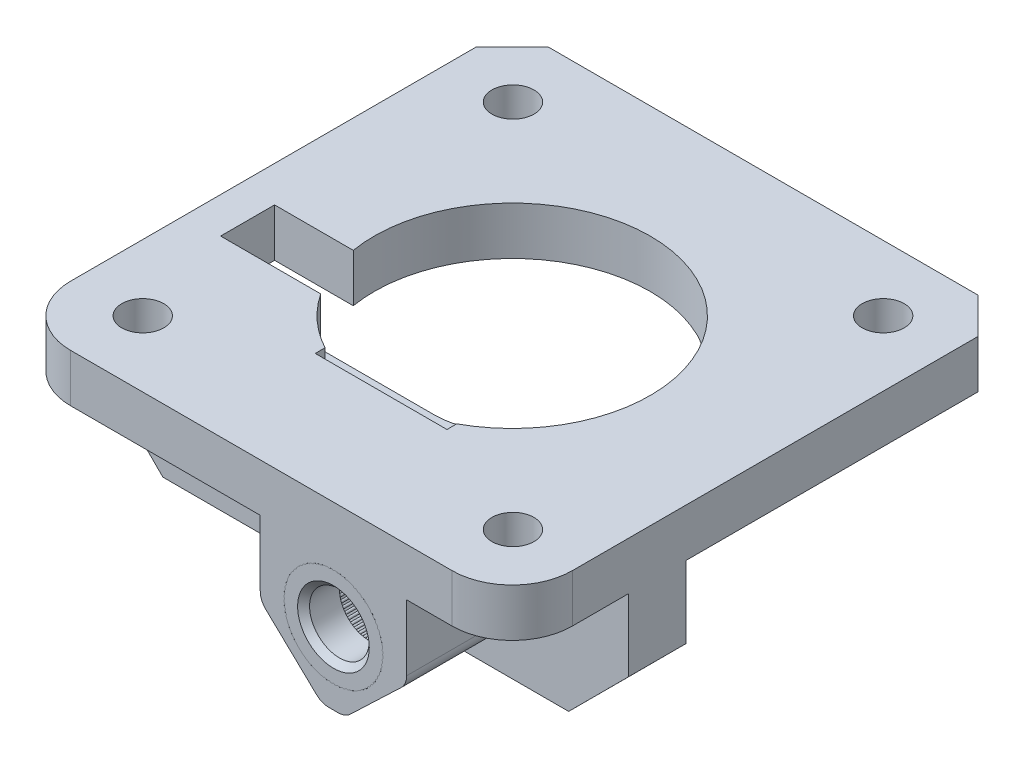
SolidWorks part; units mm, degrees
material "1060 Alloy"
ref_plane "Front Plane" through (0, 0, 0) normal (0, 0, 1) x (1, 0, 0)
ref_plane "Top Plane" through (0, 0, 0) normal (0, 1, 0) x (1, 0, 0)
ref_plane "Right Plane" through (0, 0, 0) normal (1, 0, 0) x (0, 0, -1)
sketch "Sketch2" plane through (0, 0, 0) normal (0, 1, 0) x (1, 0, 0)
  line L0 (-21, 18.0019) -> (-18.0019, 21)
  line L1 (18.0019, 21) -> (-18.0019, 21)
  line L2 (21, 18.0019) -> (21, -15.97)
  line L3 (15.97, -21) -> (-15.97, -21)
  line L4 (-21, 18.0019) -> (-21, -15.97)
  line L5 (19.5009, 19.5009) -> (-21, -21) construction
  line L6 (21, -21) -> (-19.5009, 19.5009) construction
  line L7 (18.0019, 21) -> (21, 18.0019)
  line L8 (-5.5162, -10.979) -> (5.5162, -10.979)
  line L9 (-5.5162, -10.979) -> (-5.5162, -10.159)
  line L10 (5.5162, -10.979) -> (5.5162, -10.159)
  line L11 (-17.99, -1.91) -> (-17.99, -6.43)
  line L12 (-17.99, -1.91) -> (-11.4011, -1.91)
  line L13 (-17.99, -6.43) -> (-9.6067, -6.43)
  arc A1 (21, -15.97) -> (15.97, -21) centre (15.97, -15.97) cw
  arc A2 (-15.97, -21) -> (-21, -15.97) centre (-15.97, -15.97) cw
  circle A4 centre (-15.47, 15.53) radius 1.76
  circle A5 centre (15.53, 15.53) radius 1.76
  circle A6 centre (-15.47, -15.47) radius 1.76
  circle A7 centre (15.53, -15.47) radius 1.76
  arc A8 (5.5162, -10.159) -> (-11.4011, -1.91) centre (0, 0) ccw
  arc A9 (-9.6067, -6.43) -> (-5.5162, -10.159) centre (0, 0) ccw
  point P0 (0, 0)
  point P10 (-19.5009, 19.5009)
  point P11 (19.5009, 19.5009)
  point P30 (0, -10.979)
  dimension "D7" = 5.03
  dimension "D8" = 3.52
  dimension "D11" = 3.52
  dimension "D12" = 5.47
  dimension "D13" = 5.47
  dimension "D14" = 3.52
  dimension "D15" = 3.52
  dimension "D16" = 5.53
  dimension "D17" = 5.53
  dimension "D20" = 23.12
  dimension "D1" = 42
  dimension "D2" = 4.24
  dimension "D3" = 4.24
  dimension "D4" = 45
  dimension "D5" = 36.0037
  dimension "D6" = 39.0019
  dimension "D9" = 5.53
  dimension "D10" = 5.47
  dimension "D18" = 5.47
  dimension "D19" = 5.53
  dimension "D21" = 11.0324
  dimension "D22" = 0.82
  dimension "D23" = 4.52
  dimension "D24" = 14.57
  dimension "D25" = 3.01
extrude "Boss-Extrude1" add sketch "Sketch2" along normal blind 4.02
ref_plane "Plane1" through (0, 0, 21) normal (0, 0, 1) x (1, 0, 0)
sketch "Sketch4" plane through (0, 0, 21) normal (0, 0, 1) x (1, 0, 0)
  line L0 (-21, 4.02) -> (-21, 0) construction
  line L1 (-15.97, 4.02) -> (15.97, 4.02) construction
  line L2 (12.16, 0) -> (12.16, -5.505)
  line L3 (7.4523, -10.6426) -> (11.6923, -6.5976)
  line L4 (6.41, -11.06) -> (5.65, -11.06)
  line L5 (4.6077, -10.6426) -> (0.3677, -6.5976)
  line L6 (-0.1, -5.505) -> (-0.1, 0)
  line L7 (-15.97, 0) -> (15.97, 0) construction
  line L8 (-0.1, 0) -> (12.16, 0)
  arc A0 (6.4951, -9.1539) -> (6.6481, -9.1337) centre (6.03, -5.03) ccw
  arc A1 (12.16, -5.505) -> (11.6923, -6.5976) centre (10.65, -5.505) cw
  arc A2 (7.4523, -10.6426) -> (6.41, -11.06) centre (6.41, -9.55) cw
  arc A3 (5.65, -11.06) -> (4.6077, -10.6426) centre (5.65, -9.55) cw
  arc A4 (0.3677, -6.5976) -> (-0.1, -5.505) centre (1.41, -5.505) cw
  arc A5 (6.1339, -9.1787) -> (5.9261, -9.1787) centre (6.03, -9.2387) ccw
  arc A6 (5.7719, -9.172) -> (5.5649, -9.1539) centre (5.6632, -9.2227) ccw
  arc A7 (5.4119, -9.1337) -> (5.2073, -9.0976) centre (5.2992, -9.1748) ccw
  arc A8 (5.0566, -9.0642) -> (4.8559, -9.0104) centre (4.9407, -9.0953) ccw
  arc A9 (4.7087, -8.964) -> (4.5134, -8.893) centre (4.5905, -8.9849) ccw
  arc A10 (4.3709, -8.8339) -> (4.1825, -8.7461) centre (4.2513, -8.8444) ccw
  arc A11 (4.0456, -8.6748) -> (3.8657, -8.5709) centre (3.9256, -8.6749) ccw
  arc A12 (3.7355, -8.488) -> (3.5653, -8.3688) centre (3.616, -8.4776) ccw
  arc A13 (3.4429, -8.2749) -> (3.2837, -8.1413) centre (3.3247, -8.2541) ccw
  arc A14 (3.1699, -8.0371) -> (3.0229, -7.8901) centre (3.054, -8.006) ccw
  arc A15 (2.9187, -7.7763) -> (2.7851, -7.6171) centre (2.8059, -7.7353) ccw
  arc A16 (2.6912, -7.4947) -> (2.572, -7.3245) centre (2.5824, -7.444) ccw
  arc A17 (2.4891, -7.1943) -> (2.3852, -7.0144) centre (2.3851, -7.1344) ccw
  arc A18 (2.3139, -6.8775) -> (2.2261, -6.6891) centre (2.2156, -6.8087) ccw
  arc A19 (2.167, -6.5466) -> (2.096, -6.3513) centre (2.0751, -6.4695) ccw
  arc A20 (2.0496, -6.2041) -> (1.9958, -6.0034) centre (1.9647, -6.1193) ccw
  arc A21 (1.9624, -5.8527) -> (1.9263, -5.6481) centre (1.8852, -5.7608) ccw
  arc A22 (1.9061, -5.4951) -> (1.888, -5.2881) centre (1.8373, -5.3968) ccw
  arc A23 (1.8813, -5.1339) -> (1.8813, -4.9261) centre (1.8213, -5.03) ccw
  arc A24 (1.888, -4.7719) -> (1.9061, -4.5649) centre (1.8373, -4.6632) ccw
  arc A25 (1.9263, -4.4119) -> (1.9624, -4.2073) centre (1.8852, -4.2992) ccw
  arc A26 (1.9958, -4.0566) -> (2.0496, -3.8559) centre (1.9647, -3.9407) ccw
  arc A27 (2.096, -3.7087) -> (2.167, -3.5134) centre (2.0751, -3.5905) ccw
  arc A28 (2.2261, -3.3709) -> (2.3139, -3.1825) centre (2.2156, -3.2513) ccw
  arc A29 (2.3852, -3.0456) -> (2.4891, -2.8657) centre (2.3851, -2.9256) ccw
  arc A30 (2.572, -2.7355) -> (2.6912, -2.5653) centre (2.5824, -2.616) ccw
  arc A31 (2.7851, -2.4429) -> (2.9187, -2.2837) centre (2.8059, -2.3247) ccw
  arc A32 (3.0229, -2.1699) -> (3.1699, -2.0229) centre (3.054, -2.054) ccw
  arc A33 (3.2837, -1.9187) -> (3.4429, -1.7851) centre (3.3247, -1.8059) ccw
  arc A34 (3.5653, -1.6912) -> (3.7355, -1.572) centre (3.616, -1.5824) ccw
  arc A35 (3.8657, -1.4891) -> (4.0456, -1.3852) centre (3.9256, -1.3851) ccw
  arc A36 (4.1825, -1.3139) -> (4.3709, -1.2261) centre (4.2513, -1.2156) ccw
  arc A37 (4.5134, -1.167) -> (4.7087, -1.096) centre (4.5905, -1.0751) ccw
  arc A38 (4.8559, -1.0496) -> (5.0566, -0.9958) centre (4.9407, -0.9647) ccw
  arc A39 (5.2073, -0.9624) -> (5.4119, -0.9263) centre (5.2992, -0.8852) ccw
  arc A40 (5.5649, -0.9061) -> (5.7719, -0.888) centre (5.6632, -0.8373) ccw
  arc A41 (5.9261, -0.8813) -> (6.1339, -0.8813) centre (6.03, -0.8213) ccw
  arc A42 (6.2881, -0.888) -> (6.4951, -0.9061) centre (6.3968, -0.8373) ccw
  arc A43 (6.6481, -0.9263) -> (6.8527, -0.9624) centre (6.7608, -0.8852) ccw
  arc A44 (7.0034, -0.9958) -> (7.2041, -1.0496) centre (7.1193, -0.9647) ccw
  arc A45 (7.3513, -1.096) -> (7.5466, -1.167) centre (7.4695, -1.0751) ccw
  arc A46 (7.6891, -1.2261) -> (7.8775, -1.3139) centre (7.8087, -1.2156) ccw
  arc A47 (8.0144, -1.3852) -> (8.1943, -1.4891) centre (8.1344, -1.3851) ccw
  arc A48 (8.3245, -1.572) -> (8.4947, -1.6912) centre (8.444, -1.5824) ccw
  arc A49 (8.6171, -1.7851) -> (8.7763, -1.9187) centre (8.7353, -1.8059) ccw
  arc A50 (8.8901, -2.0229) -> (9.0371, -2.1699) centre (9.006, -2.054) ccw
  arc A51 (9.1413, -2.2837) -> (9.2749, -2.4429) centre (9.2541, -2.3247) ccw
  arc A52 (9.3688, -2.5653) -> (9.488, -2.7355) centre (9.4776, -2.616) ccw
  arc A53 (9.5709, -2.8657) -> (9.6748, -3.0456) centre (9.6749, -2.9256) ccw
  arc A54 (9.7461, -3.1825) -> (9.8339, -3.3709) centre (9.8444, -3.2513) ccw
  arc A55 (9.893, -3.5134) -> (9.964, -3.7087) centre (9.9849, -3.5905) ccw
  arc A56 (10.0104, -3.8559) -> (10.0642, -4.0566) centre (10.0953, -3.9407) ccw
  arc A57 (10.0976, -4.2073) -> (10.1337, -4.4119) centre (10.1748, -4.2992) ccw
  arc A58 (10.1539, -4.5649) -> (10.172, -4.7719) centre (10.2227, -4.6632) ccw
  arc A59 (10.1787, -4.9261) -> (10.1787, -5.1339) centre (10.2387, -5.03) ccw
  arc A60 (10.172, -5.2881) -> (10.1539, -5.4951) centre (10.2227, -5.3968) ccw
  arc A61 (10.1337, -5.6481) -> (10.0976, -5.8527) centre (10.1748, -5.7608) ccw
  arc A62 (10.0642, -6.0034) -> (10.0104, -6.2041) centre (10.0953, -6.1193) ccw
  arc A63 (9.964, -6.3513) -> (9.893, -6.5466) centre (9.9849, -6.4695) ccw
  arc A64 (9.8339, -6.6891) -> (9.7461, -6.8775) centre (9.8444, -6.8087) ccw
  arc A65 (9.6748, -7.0144) -> (9.5709, -7.1943) centre (9.6749, -7.1344) ccw
  arc A66 (9.488, -7.3245) -> (9.3688, -7.4947) centre (9.4776, -7.444) ccw
  arc A67 (9.2749, -7.6171) -> (9.1413, -7.7763) centre (9.2541, -7.7353) ccw
  arc A68 (9.0371, -7.8901) -> (8.8901, -8.0371) centre (9.006, -8.006) ccw
  arc A69 (8.7763, -8.1413) -> (8.6171, -8.2749) centre (8.7353, -8.2541) ccw
  arc A70 (8.4947, -8.3688) -> (8.3245, -8.488) centre (8.444, -8.4776) ccw
  arc A71 (8.1943, -8.5709) -> (8.0144, -8.6748) centre (8.1344, -8.6749) ccw
  arc A72 (7.8775, -8.7461) -> (7.6891, -8.8339) centre (7.8087, -8.8444) ccw
  arc A73 (7.5466, -8.893) -> (7.3513, -8.964) centre (7.4695, -8.9849) ccw
  arc A74 (7.2041, -9.0104) -> (7.0034, -9.0642) centre (7.1193, -9.0953) ccw
  arc A75 (6.8527, -9.0976) -> (6.6481, -9.1337) centre (6.7608, -9.1748) ccw
  arc A76 (6.4951, -9.1539) -> (6.2881, -9.172) centre (6.3968, -9.2227) ccw
  arc A77 (6.8527, -9.0976) -> (7.0034, -9.0642) centre (6.03, -5.03) ccw
  arc A78 (6.1339, -9.1787) -> (6.2881, -9.172) centre (6.03, -5.03) ccw
  arc A79 (5.7719, -9.172) -> (5.9261, -9.1787) centre (6.03, -5.03) ccw
  arc A80 (5.4119, -9.1337) -> (5.5649, -9.1539) centre (6.03, -5.03) ccw
  arc A81 (5.0566, -9.0642) -> (5.2073, -9.0976) centre (6.03, -5.03) ccw
  arc A82 (4.7087, -8.964) -> (4.8559, -9.0104) centre (6.03, -5.03) ccw
  arc A83 (4.3709, -8.8339) -> (4.5134, -8.893) centre (6.03, -5.03) ccw
  arc A84 (4.0456, -8.6748) -> (4.1825, -8.7461) centre (6.03, -5.03) ccw
  arc A85 (3.7355, -8.488) -> (3.8657, -8.5709) centre (6.03, -5.03) ccw
  arc A86 (3.4429, -8.2749) -> (3.5653, -8.3688) centre (6.03, -5.03) ccw
  arc A87 (3.1699, -8.0371) -> (3.2837, -8.1413) centre (6.03, -5.03) ccw
  arc A88 (2.9187, -7.7763) -> (3.0229, -7.8901) centre (6.03, -5.03) ccw
  arc A89 (2.6912, -7.4947) -> (2.7851, -7.6171) centre (6.03, -5.03) ccw
  arc A90 (2.4891, -7.1943) -> (2.572, -7.3245) centre (6.03, -5.03) ccw
  arc A91 (2.3139, -6.8775) -> (2.3852, -7.0144) centre (6.03, -5.03) ccw
  arc A92 (2.167, -6.5466) -> (2.2261, -6.6891) centre (6.03, -5.03) ccw
  arc A93 (2.0496, -6.2041) -> (2.096, -6.3513) centre (6.03, -5.03) ccw
  arc A94 (1.9624, -5.8527) -> (1.9958, -6.0034) centre (6.03, -5.03) ccw
  arc A95 (1.9061, -5.4951) -> (1.9263, -5.6481) centre (6.03, -5.03) ccw
  arc A96 (1.8813, -5.1339) -> (1.888, -5.2881) centre (6.03, -5.03) ccw
  arc A97 (1.888, -4.7719) -> (1.8813, -4.9261) centre (6.03, -5.03) ccw
  arc A98 (1.9263, -4.4119) -> (1.9061, -4.5649) centre (6.03, -5.03) ccw
  arc A99 (1.9958, -4.0566) -> (1.9624, -4.2073) centre (6.03, -5.03) ccw
  arc A100 (2.096, -3.7087) -> (2.0496, -3.8559) centre (6.03, -5.03) ccw
  arc A101 (2.2261, -3.3709) -> (2.167, -3.5134) centre (6.03, -5.03) ccw
  arc A102 (2.3852, -3.0456) -> (2.3139, -3.1825) centre (6.03, -5.03) ccw
  arc A103 (2.572, -2.7355) -> (2.4891, -2.8657) centre (6.03, -5.03) ccw
  arc A104 (2.7851, -2.4429) -> (2.6912, -2.5653) centre (6.03, -5.03) ccw
  arc A105 (3.0229, -2.1699) -> (2.9187, -2.2837) centre (6.03, -5.03) ccw
  arc A106 (4.8559, -1.0496) -> (4.7087, -1.096) centre (6.03, -5.03) ccw
  arc A107 (4.5134, -1.167) -> (4.3709, -1.2261) centre (6.03, -5.03) ccw
  arc A108 (4.1825, -1.3139) -> (4.0456, -1.3852) centre (6.03, -5.03) ccw
  arc A109 (3.8657, -1.4891) -> (3.7355, -1.572) centre (6.03, -5.03) ccw
  arc A110 (3.5653, -1.6912) -> (3.4429, -1.7851) centre (6.03, -5.03) ccw
  arc A111 (3.2837, -1.9187) -> (3.1699, -2.0229) centre (6.03, -5.03) ccw
  arc A112 (5.2073, -0.9624) -> (5.0566, -0.9958) centre (6.03, -5.03) ccw
  arc A113 (5.5649, -0.9061) -> (5.4119, -0.9263) centre (6.03, -5.03) ccw
  arc A114 (5.9261, -0.8813) -> (5.7719, -0.888) centre (6.03, -5.03) ccw
  arc A115 (6.2881, -0.888) -> (6.1339, -0.8813) centre (6.03, -5.03) ccw
  arc A116 (6.6481, -0.9263) -> (6.4951, -0.9061) centre (6.03, -5.03) ccw
  arc A117 (7.0034, -0.9958) -> (6.8527, -0.9624) centre (6.03, -5.03) ccw
  arc A118 (7.3513, -1.096) -> (7.2041, -1.0496) centre (6.03, -5.03) ccw
  arc A119 (7.6891, -1.2261) -> (7.5466, -1.167) centre (6.03, -5.03) ccw
  arc A120 (8.0144, -1.3852) -> (7.8775, -1.3139) centre (6.03, -5.03) ccw
  arc A121 (8.3245, -1.572) -> (8.1943, -1.4891) centre (6.03, -5.03) ccw
  arc A122 (8.6171, -1.7851) -> (8.4947, -1.6912) centre (6.03, -5.03) ccw
  arc A123 (8.8901, -2.0229) -> (8.7763, -1.9187) centre (6.03, -5.03) ccw
  arc A124 (9.1413, -2.2837) -> (9.0371, -2.1699) centre (6.03, -5.03) ccw
  arc A125 (9.3688, -2.5653) -> (9.2749, -2.4429) centre (6.03, -5.03) ccw
  arc A126 (9.5709, -2.8657) -> (9.488, -2.7355) centre (6.03, -5.03) ccw
  arc A127 (9.7461, -3.1825) -> (9.6748, -3.0456) centre (6.03, -5.03) ccw
  arc A128 (9.893, -3.5134) -> (9.8339, -3.3709) centre (6.03, -5.03) ccw
  arc A129 (10.0104, -3.8559) -> (9.964, -3.7087) centre (6.03, -5.03) ccw
  arc A130 (10.0976, -4.2073) -> (10.0642, -4.0566) centre (6.03, -5.03) ccw
  arc A131 (10.1539, -4.5649) -> (10.1337, -4.4119) centre (6.03, -5.03) ccw
  arc A132 (10.1787, -4.9261) -> (10.172, -4.7719) centre (6.03, -5.03) ccw
  arc A133 (10.172, -5.2881) -> (10.1787, -5.1339) centre (6.03, -5.03) ccw
  arc A134 (10.1337, -5.6481) -> (10.1539, -5.4951) centre (6.03, -5.03) ccw
  arc A135 (10.0642, -6.0034) -> (10.0976, -5.8527) centre (6.03, -5.03) ccw
  arc A136 (9.964, -6.3513) -> (10.0104, -6.2041) centre (6.03, -5.03) ccw
  arc A137 (9.8339, -6.6891) -> (9.893, -6.5466) centre (6.03, -5.03) ccw
  arc A138 (9.6748, -7.0144) -> (9.7461, -6.8775) centre (6.03, -5.03) ccw
  arc A139 (9.488, -7.3245) -> (9.5709, -7.1943) centre (6.03, -5.03) ccw
  arc A140 (9.2749, -7.6171) -> (9.3688, -7.4947) centre (6.03, -5.03) ccw
  arc A141 (9.0371, -7.8901) -> (9.1413, -7.7763) centre (6.03, -5.03) ccw
  arc A142 (8.7763, -8.1413) -> (8.8901, -8.0371) centre (6.03, -5.03) ccw
  arc A143 (8.4947, -8.3688) -> (8.6171, -8.2749) centre (6.03, -5.03) ccw
  arc A144 (8.1943, -8.5709) -> (8.3245, -8.488) centre (6.03, -5.03) ccw
  arc A145 (7.8775, -8.7461) -> (8.0144, -8.6748) centre (6.03, -5.03) ccw
  arc A146 (7.5466, -8.893) -> (7.6891, -8.8339) centre (6.03, -5.03) ccw
  arc A147 (7.2041, -9.0104) -> (7.3513, -8.964) centre (6.03, -5.03) ccw
  point P15 (6.03, -11.06)
  point P24 (6.03, -9.1187)
  point P28 (6.1339, -9.1787)
  point P243 (6.03, -5.03)
  dimension "D5" = 1.51
  dimension "D6" = 1.51
  dimension "D7" = 1.51
  dimension "D8" = 1.51
  dimension "D12" = 8.3
  dimension "D13" = 0.2078
  dimension ".24" = 0.24
  dimension "D14" = 72
  dimension "D1" = 27.03
  dimension "D2" = 9.05
  dimension "D3" = 6.13
  dimension "D4" = 6.03
  dimension "D9" = 6.13
  dimension "D10" = 0.76
  dimension "D11" = 5.86
sketch "Sketch5" plane through (0, 0, 21) normal (0, 0, 1) x (1, 0, 0)
  line L0 (4.6077, -10.6426) -> (0.3677, -6.5976) construction
  line L1 (7.4523, -10.6426) -> (11.6923, -6.5976) construction
  line L2 (6.41, -11.06) -> (5.65, -11.06) construction
  line L3 (12.16, 0) -> (12.16, -5.505) construction
  line L4 (-0.1, 0) -> (12.16, 0) construction
  line L5 (-0.1, -5.505) -> (-0.1, 0) construction
  line L6 (4.6077, -10.6426) -> (0.3677, -6.5976)
  line L7 (7.4523, -10.6426) -> (11.6923, -6.5976)
  line L8 (6.41, -11.06) -> (5.65, -11.06)
  line L9 (12.16, 0) -> (12.16, -5.505)
  line L10 (-0.1, 0) -> (12.16, 0)
  line L11 (-0.1, -5.505) -> (-0.1, 0)
  arc A0 (-0.1, -5.505) -> (0.3677, -6.5976) centre (1.41, -5.505) ccw construction
  arc A1 (6.41, -11.06) -> (7.4523, -10.6426) centre (6.41, -9.55) ccw construction
  arc A2 (4.6077, -10.6426) -> (5.65, -11.06) centre (5.65, -9.55) ccw construction
  arc A3 (11.6923, -6.5976) -> (12.16, -5.505) centre (10.65, -5.505) ccw construction
  arc A4 (-0.1, -5.505) -> (0.3677, -6.5976) centre (1.41, -5.505) ccw
  arc A5 (6.41, -11.06) -> (7.4523, -10.6426) centre (6.41, -9.55) ccw
  arc A6 (4.6077, -10.6426) -> (5.65, -11.06) centre (5.65, -9.55) ccw
  arc A7 (11.6923, -6.5976) -> (12.16, -5.505) centre (10.65, -5.505) ccw
extrude "Boss-Extrude3" add sketch "Sketch5" against normal blind 9.75
extrude "Cut-Extrude2" cut sketch "Sketch4" against normal blind 9.75 contours A74 A147 A73 A146 A72 A145 A71 A144 A70 A143 A69 A142 A68 A141 A67 A140 A66 A139 A65 A138 A64 A137 A63 A136 A62 A135 A61 A134 A60 A133 A59 A132 A58 A131 A57 A130 A56 A129 A55 A128 A54 A127 A53 A126 A52 A125 A51 A124 A50 A123 A49
sketch "Sketch7" plane through (0, 0, 21) normal (0, 0, 1) x (1, 0, 0)
  circle A0 centre (6.03, -5.03) radius 2.5
  circle A1 centre (6.03, -5.03) radius 4.15
  dimension "D1" = 5
extrude "Boss-Extrude4" add sketch "Sketch7" against normal blind 3 separate body
chamfer "Chamfer1" distance 0.5 angle 45 1 edges at (8.53, -5.03, 21)
sketch "Sketch8" plane through (21, 0, 0) normal (1, 0, 0) x (0, 0, -1)
  line L1 (-11.25, 0) -> (-6.43, 0)
  line L2 (-11.25, 0) -> (-11.25, -11.06)
  line L3 (-11.25, -11.06) -> (-6.43, -11.06)
  line L4 (-6.43, 0) -> (-6.43, -11.06)
  dimension "D1" = 4.82
  dimension "D2" = 11.06
extrude "Boss-Extrude5" add sketch "Sketch8" against normal up to surface (42 mm away) up to face at (-21, 2.01, -1.0159)
sketch "Sketch9" plane through (0, 0, 11.25) normal (0, 0, 1) x (1, 0, 0)
  line L0 (21, -6.03) -> (15.9749, -11.06)
  line L1 (21, 0) -> (21, -11.06) construction
  line L2 (6.41, -11.06) -> (21, -11.06) construction
  dimension "D1" = 5.03
  dimension "D2" = 7.11
extrude "Cut-Extrude3" cut sketch "Sketch9" against normal through all and the other way through all
sketch "Sketch10" plane through (0, 0, 11.25) normal (0, 0, 1) x (1, 0, 0)
  line L0 (-21, -8.06) -> (-18.0037, -11.06)
  line L1 (-21, -11.06) -> (-21, 0) construction
  line L2 (-21, -11.06) -> (5.65, -11.06) construction
  dimension "D1" = 3
  dimension "D2" = 4.24
extrude "Cut-Extrude5" cut sketch "Sketch10" against normal through all and the other way through all flip side to cut
sketch "Sketch11" plane through (0, 0, 0) normal (0, -1, 0) x (1, 0, 0)
  line L0 (-9.6067, 6.43) -> (-0.0267, 6.43) construction
  line L1 (-9.6067, 6.43) -> (9.6067, 6.43) construction
  line L2 (21, 6.43) -> (12.16, 6.43) construction
  line L3 (9.6067, 6.43) -> (21, 6.43) construction
  line L4 (4.4716, 3.959) -> (7.6616, 3.959)
  line L5 (12.16, 6.43) -> (-0.0267, 6.43)
  arc A0 (-0.0267, 6.43) -> (4.4716, 3.959) centre (-0.0267, 1.1) cw
  arc A1 (12.16, 6.43) -> (7.6616, 3.959) centre (12.16, 1.1) ccw
  dimension "D3" = 5.33
  dimension "D4" = 5.33
  dimension "D1" = 9.58
  dimension "D2" = 8.84
  dimension "D5" = 3.19
extrude "Boss-Extrude6" add sketch "Sketch11" along normal up to surface (11.06 mm away) up to face at (2.5078, -11.06, 12.4825)
sketch "Sketch12" plane through (0, 0, 3.959) normal (0, 0, -1) x (-1, 0, 0)
  line L1 (-4.4716, -11.06) -> (-7.6616, -11.06) construction
  line L2 (-4.4716, 0) -> (-7.6616, 0) construction
  circle A0 centre (-6.0666, -5.03) radius 1.405
  point P4 (-6.0666, -11.06)
  dimension "D1" = 2.81
  dimension "D2" = 5.03
extrude "Cut-Extrude6" cut sketch "Sketch12" against normal through all
sketch "Sketch13" plane through (0, 0, 6.43) normal (0, 0, -1) x (-1, 0, 0)
  line L0 (21, 0) -> (21, -8.06) construction
  line L1 (18.0037, -11.06) -> (0.0267, -11.06) construction
  circle A0 centre (14.88, -5.53) radius 2.515
  dimension "D1" = 5.03
  dimension "D3" = 5.53
  dimension "D2" = 6.12
extrude "Boss-Extrude7" add sketch "Sketch13" along normal blind 3.02
chamfer "Chamfer2" distance 0.75 angle 45 1 edges at (-17.395, -5.53, 3.41)
chamfer "Chamfer3" distance 1 angle 45 1 edges at (-15.47, 0, -13.77)
fillet "Fillet1" radius 0.25 2 edges at (7.6616, -5.53, 3.959) (4.4716, -5.53, 3.959)
